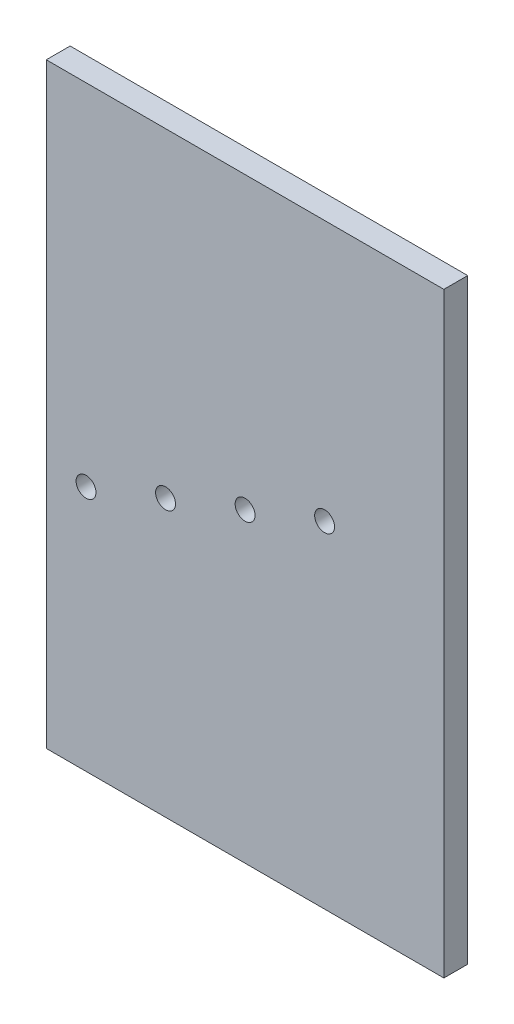
SolidWorks part; units mm, degrees
ref_plane "Plan de face" through (0, 0, 0) normal (0, 0, 1) x (1, 0, 0)
ref_plane "Plan de dessus" through (0, 0, 0) normal (0, 1, 0) x (1, 0, 0)
ref_plane "Plan de droite" through (0, 0, 0) normal (1, 0, 0) x (0, 0, -1)
sketch "Esquisse1" plane through (0, 0, 0) normal (0, 0, 1) x (1, 0, 0)
  line L0 (-100, 0) -> (-100, 150)
  line L1 (0, 0) -> (-100, 0)
  line L2 (0, 0) -> (0, 150)
  line L3 (-100, 150) -> (0, 150)
  dimension "D1" = 90
  dimension "D2" = 100
  dimension "D3" = 150
extrude "Boss.-Extru.1" add sketch "Esquisse1" along normal blind 6
sketch "Esquisse2" plane through (0, 0, 6) normal (0, 0, 1) x (1, 0, 0)
  line L1 (-100, 150) -> (-100, 0) construction
  line L2 (-100, 0) -> (0, 0) construction
  circle A0 centre (-90, 62) radius 2.5
  circle A1 centre (-70, 69.5) radius 2.5
  circle A2 centre (-30, 84.5) radius 2.5
  circle A3 centre (-50, 77) radius 2.5
  dimension "D1" = 5
  dimension "D2" = 5
  dimension "D3" = 5
  dimension "D5" = 69.5
  dimension "D10" = 5
  dimension "D4" = 62
  dimension "D6" = 77
  dimension "D7" = 10
  dimension "D8" = 20
  dimension "D9" = 20
  dimension "D11" = 84.5
  dimension "D12" = 20
extrude "Enlèv. mat.-Extru.1" cut sketch "Esquisse2" against normal blind 10
